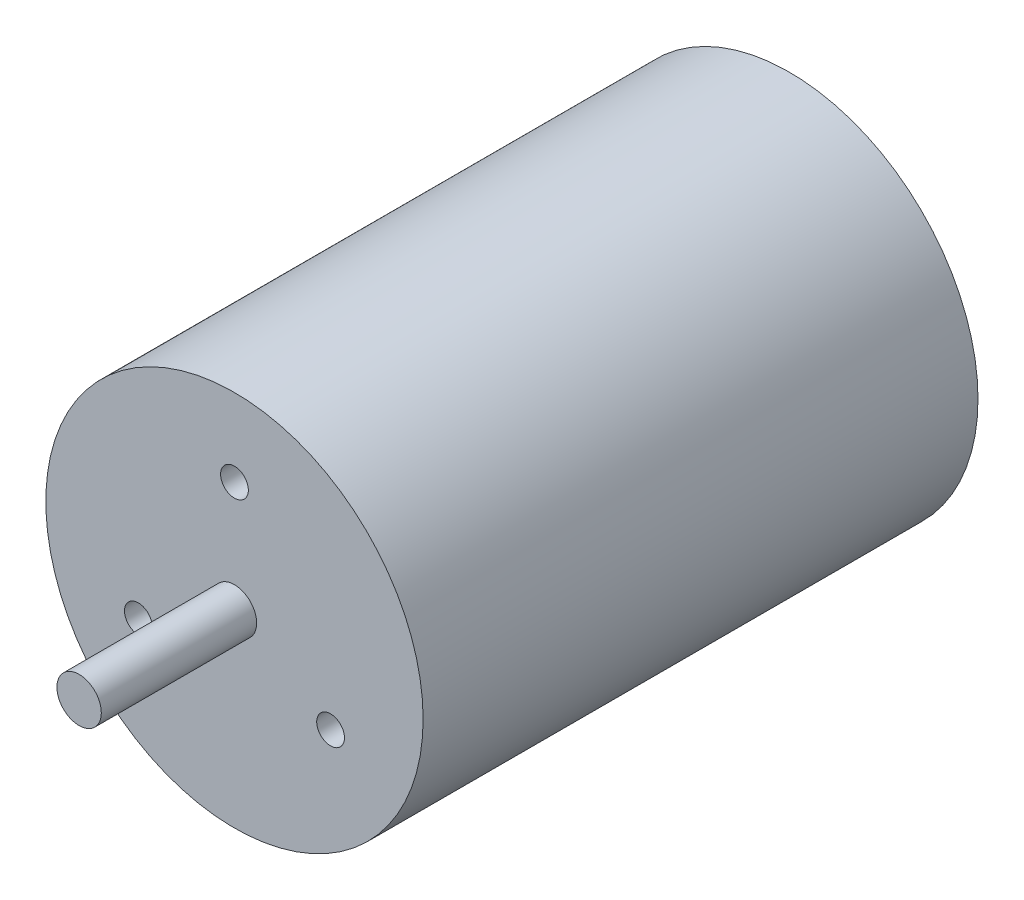
SolidWorks part; units mm, degrees
ref_plane "Front Plane" through (0, 0, 0) normal (0, 0, 1) x (1, 0, 0)
ref_plane "Top Plane" through (0, 0, 0) normal (0, 1, 0) x (1, 0, 0)
ref_plane "Right Plane" through (0, 0, 0) normal (1, 0, 0) x (0, 0, -1)
sketch "Sketch1" plane through (0, 0, 0) normal (0, 0, 1) x (1, 0, 0)
  circle A0 centre (0, 0) radius 34
  dimension "D1" = 68
extrude "Boss-Extrude1" add sketch "Sketch1" along normal blind 100
sketch "Sketch3" plane through (0, 0, 100) normal (0, 0, 1) x (1, 0, 0)
  circle A0 centre (0, 0) radius 4
  dimension "D1" = 8
extrude "Boss-Extrude2" add sketch "Sketch3" along normal blind 28
sketch "Sketch4" plane through (0, 0, 100) normal (0, 0, 1) x (1, 0, 0)
  circle A0 centre (0, 0) radius 20 construction
  circle A1 centre (0, 0) radius 34 construction
  point P3 (0, 20)
  point P4 (17.3205, -10)
  point P7 (-17.3205, -10)
  point P8 (0, 0)
  dimension "D1" = 40
  dimension "D2" = 3
hole_wizard "M6x1.0 Tapped Hole1" positions "3DSketch1" profile "Sketch5" tap size "M6x1.0" standard "ANSI Metric"
sketch3d "3DSketch1"
  point P0 (0, 20, 100)
  point P3 (17.3205, -10, 100)
  point P6 (-17.3205, -10, 100)
sketch "Sketch5" plane through (0, 20, 100) normal (1, 0, 0) x (0, -1, 0)
  line L0 (0, 0) -> (0, 16.5009)
  line L1 (0, 16.5009) -> (2.5, 14.9987)
  line L2 (2.5, 14.9987) -> (2.5, 0)
  line L5 (2.5, 0) -> (0, 0)
  line L10 (0, 16.5009) -> (-2.5, 14.9987) construction
  line L11 (0, -6.35) -> (0, 107.95) construction
  dimension "Tap Drill Dia." = 5
  dimension "Tap Drill Depth" = 14.9987
  dimension "Drill Angle" = 118
cosmetic thread "Hole Thread1" parameters "D1"=11.999, "D2"=6
cosmetic thread "Hole Thread2" parameters "D1"=11.999, "D2"=6
cosmetic thread "Hole Thread3" parameters "D1"=11.999, "D2"=6
sketch "Sketch6" plane through (0, 0, 0) normal (0, 0, -1) x (-1, 0, 0)
  circle A0 centre (0, 0) radius 15
  dimension "D1" = 30
extrude "Boss-Extrude3" add sketch "Sketch6" along normal blind 8
